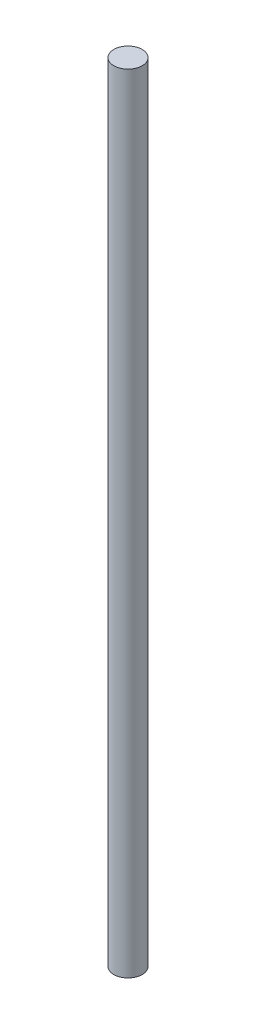
SolidWorks part; units mm, degrees
ref_plane "Front Plane" through (0, 0, 0) normal (0, 0, 1) x (1, 0, 0)
ref_plane "Top Plane" through (0, 0, 0) normal (0, 1, 0) x (1, 0, 0)
ref_plane "Right Plane" through (0, 0, 0) normal (1, 0, 0) x (0, 0, -1)
sketch "Sketch1" plane through (0, 0, 0) normal (0, 1, 0) x (1, 0, 0)
  circle A0 centre (0, 0) radius 2
  dimension "D1" = 4
extrude "Boss-Extrude1" add sketch "Sketch1" along normal blind 111
